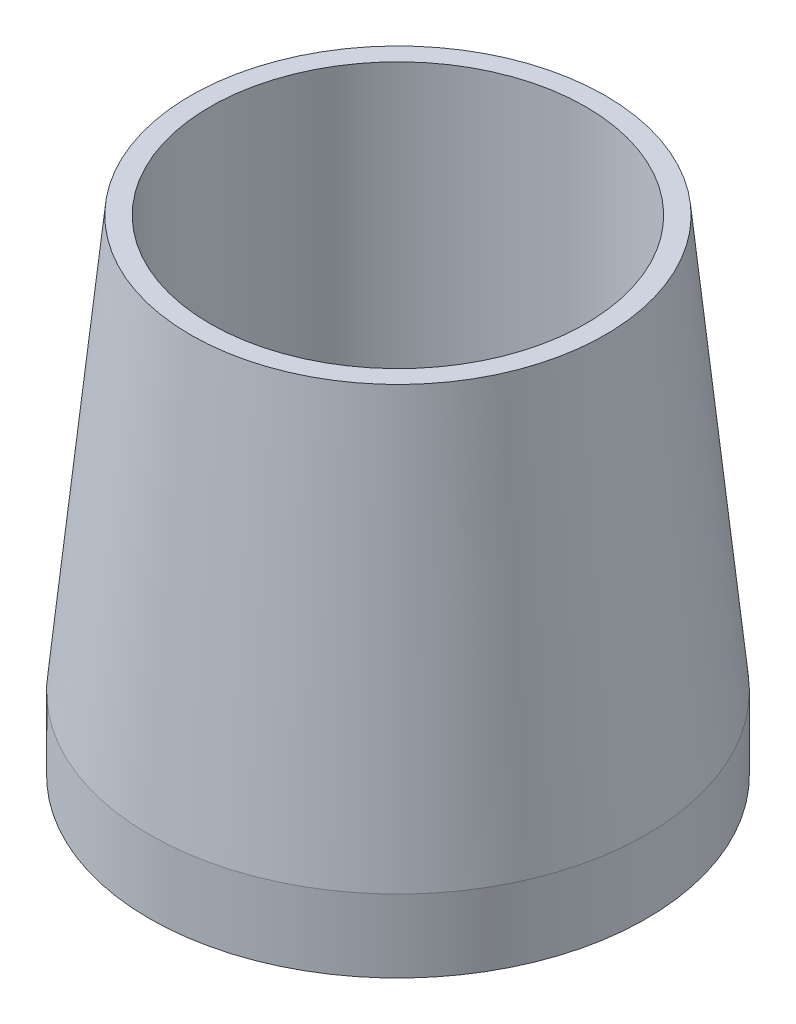
SolidWorks part; units mm, degrees
ref_plane "Front Plane" through (0, 0, 0) normal (1, 0, 0) x (0, 1, 0)
ref_plane "Top Plane" through (0, 0, 0) normal (0, 0, 1) x (0, 1, 0)
ref_plane "Right Plane" through (0, 0, 0) normal (0, 1, 0) x (-1, 0, 0)
sketch "Sketch1" plane through (0, 0, 0) normal (1, 0, 0) x (0, 1, 0)
  line L0 (0, 0) -> (0, 5.125)
  line L1 (0, 5.125) -> (1.5, 5.125)
  line L2 (1.5, 5.125) -> (10, 4.275)
  line L3 (10, 4.275) -> (10, 3.875)
  line L4 (10, 3.875) -> (1.5, 3.875)
  line L5 (1.5, 3.875) -> (1.5, 0)
  line L6 (1.5, 0) -> (0, 0)
  dimension "D1" = 5.125
  dimension "D2" = 1.5
  dimension "D3" = 10
  dimension "D4" = 1.5
  dimension "D5" = 1.25
  dimension "D6" = 0.4
  dimension "D7" = 3.875
revolve "Revolve1" add sketch "Sketch1" angle 360 about L6
sketch "Sketch2" plane through (0, 0, 0) normal (0, -1, 0) x (1, 0, 0)
  circle A0 centre (0, 0) radius 1.5
  dimension "D1" = 3
extrude "Cut-Extrude1" cut sketch "Sketch2" against normal through all
